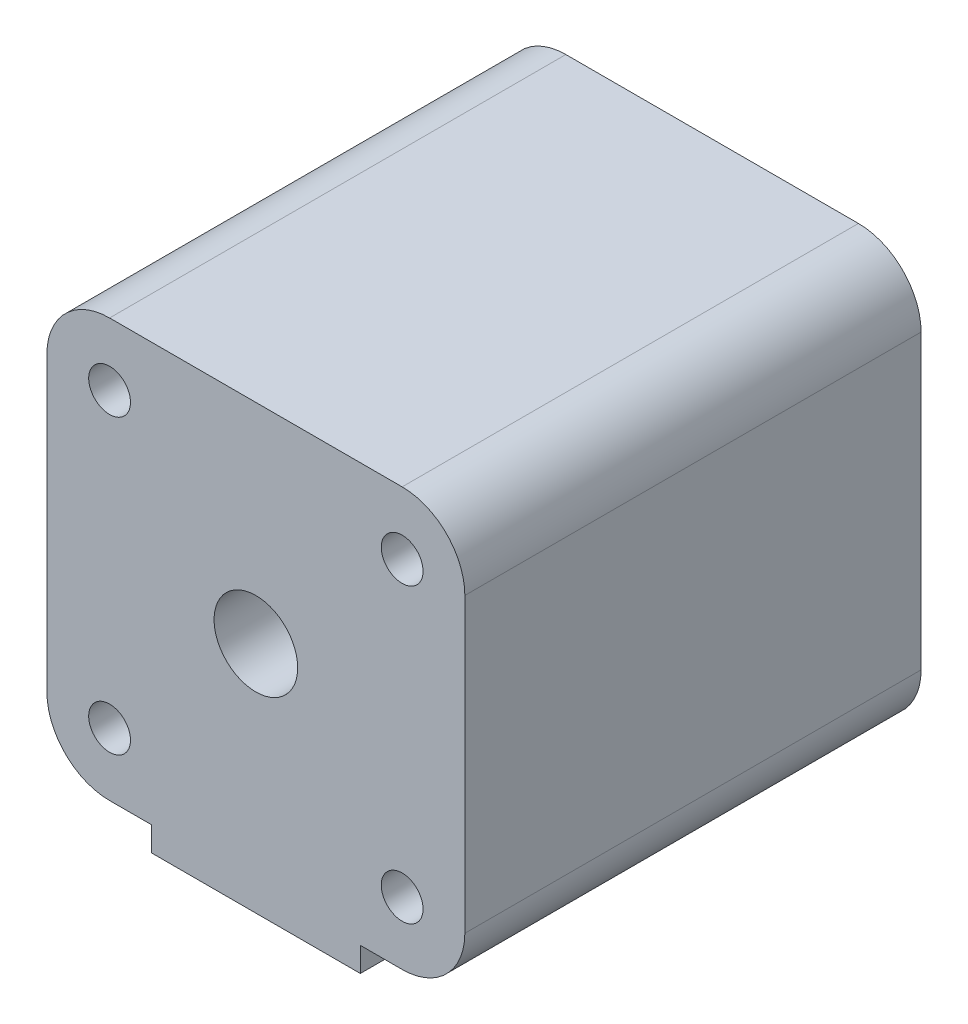
SolidWorks part; units mm, degrees
ref_plane "Alzado" through (0, 0, 0) normal (0, 0, 1) x (1, 0, 0)
ref_plane "Planta" through (0, 0, 0) normal (0, 1, 0) x (1, 0, 0)
ref_plane "Vista lateral" through (0, 0, 0) normal (1, 0, 0) x (0, 0, -1)
sketch "Croquis1" plane through (0, 0, 0) normal (0, 0, 1) x (1, 0, 0)
  line L0 (-15, -30) -> (-15, -33.5)
  line L1 (-21, 30) -> (21, 30)
  line L2 (-30, 21) -> (-30, -21)
  line L3 (-21, -30) -> (-15, -30)
  line L4 (30, 21) -> (30, -21)
  line L5 (-30, 30) -> (30, -30) construction
  line L6 (-30, -30) -> (30, 30) construction
  line L7 (-15, -33.5) -> (15, -33.5)
  line L8 (15, -33.5) -> (15, -30)
  line L9 (15, -30) -> (21, -30)
  arc A0 (21, 30) -> (30, 21) centre (21, 21) cw
  arc A1 (30, -21) -> (21, -30) centre (21, -21) cw
  arc A2 (-21, -30) -> (-30, -21) centre (-21, -21) cw
  arc A3 (-21, 30) -> (-30, 21) centre (-21, 21) ccw
  point P0 (0, 0)
  dimension "D3" = 9
  dimension "D1" = 60
  dimension "D2" = 60
  dimension "D4" = 15
  dimension "D5" = 15
  dimension "D6" = 3.5
extrude "Saliente-Extruir1" add sketch "Croquis1" against normal blind 65.5
sketch "Croquis2" plane through (0, 0, 0) normal (0, 0, 1) x (1, 0, 0)
  circle A0 centre (-21, 21) radius 3
  circle A1 centre (21, 21) radius 3
  circle A2 centre (21, -21) radius 3
  circle A3 centre (-21, -21) radius 3
  dimension "D1" = 6
  dimension "D2" = 6
  dimension "D3" = 6
  dimension "D4" = 6
extrude "Cortar-Extruir1" cut sketch "Croquis2" against normal blind 20
sketch "Croquis3" plane through (0, 0, 0) normal (0, 0, 1) x (1, 0, 0)
  circle A0 centre (0, 0) radius 6
  dimension "D1" = 12
extrude "Cortar-Extruir2" cut sketch "Croquis3" against normal blind 20
sketch "Croquis4" plane through (0, -33.5, 0) normal (0, -1, 0) x (1, 0, 0)
  line L0 (-15, 0) -> (15, 0) construction
  line L1 (-15, -65.5) -> (15, -65.5) construction
  circle A0 centre (0, -5.5) radius 4.5
  circle A1 centre (0, -60) radius 4.5
  dimension "D1" = 9
  dimension "D2" = 9
  dimension "D3" = 5.5
  dimension "D4" = 5.5
extrude "Cortar-Extruir3" cut sketch "Croquis4" against normal blind 6
